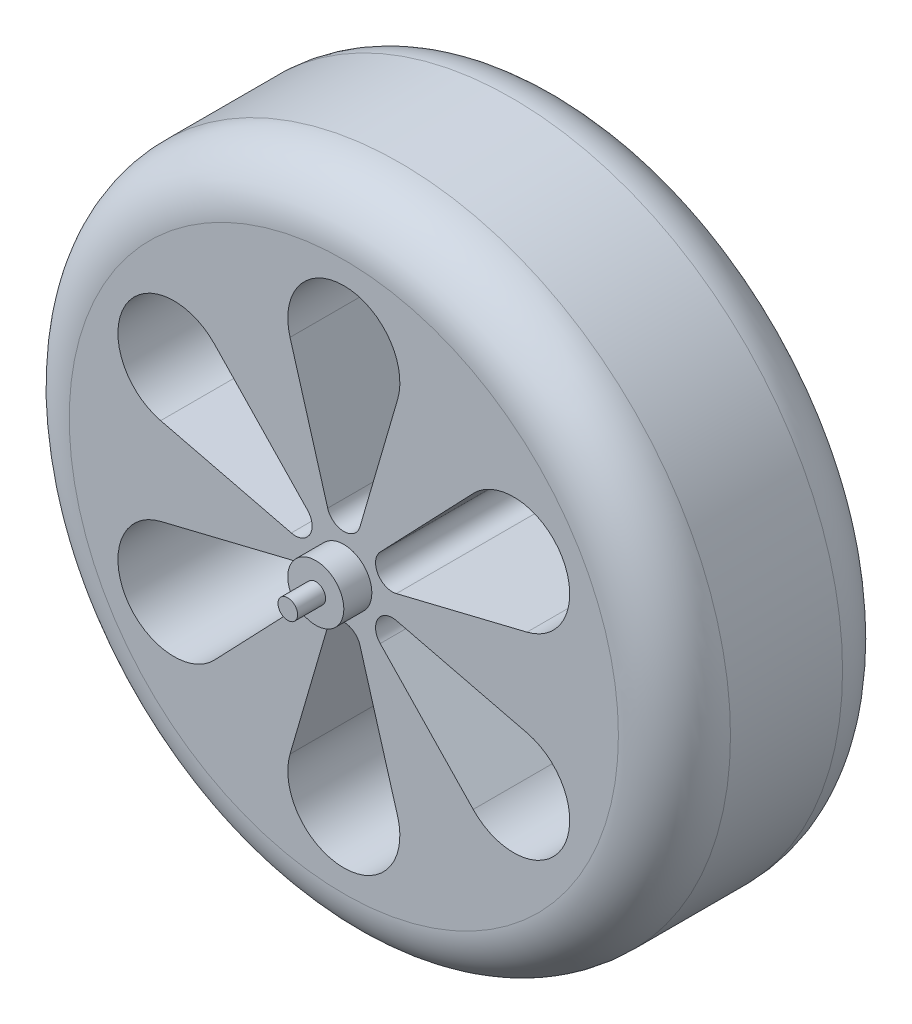
SolidWorks part; units mm, degrees
ref_plane "前视基准面" through (0, 0, 0) normal (0, 0, 1) x (1, 0, 0)
ref_plane "上视基准面" through (0, 0, 0) normal (0, 1, 0) x (1, 0, 0)
ref_plane "右视基准面" through (0, 0, 0) normal (1, 0, 0) x (0, 0, -1)
sketch "草图1" plane through (0, 0, 0) normal (0, 0, 1) x (1, 0, 0)
  circle A0 centre (0, 0) radius 59
  dimension "D1" = 118
extrude "凸台-拉伸1" add sketch "草图1" along normal blind 40
fillet "圆角1" radius 10 2 edges at (59, 0, 0) (59, 0, 40)
sketch "草图2" plane through (0, 0, 40) normal (0, 0, 1) x (1, 0, 0)
  circle A0 centre (0, 0) radius 5
  dimension "D1" = 10
extrude "凸台-拉伸2" add sketch "草图2" along normal blind 5
sketch "草图3" plane through (0, 0, 45) normal (0, 0, 1) x (1, 0, 0)
  circle A0 centre (0, 0) radius 1.75
  dimension "D1" = 3.5
extrude "凸台-拉伸3" add sketch "草图3" along normal blind 5
sketch "草图4" plane through (0, 0, 40) normal (0, 0, 1) x (1, 0, 0)
  line L0 (-9.6, 32.2) -> (-2.88, 9.16)
  line L1 (9.6, 32.2) -> (2.88, 9.16)
  arc A0 (9.6, 32.2) -> (-9.6, 32.2) centre (0, 35) ccw
  arc A1 (-2.88, 9.16) -> (2.88, 9.16) centre (0, 10) ccw
  dimension "D1" = 20
  dimension "D2" = 6
  dimension "D3" = 10
  dimension "D4" = 25
extrude "切除-拉伸1" cut sketch "草图4" against normal through all
pattern_circular "阵列(圆周)1" count 6 over 360 about axis through (0, 0, 0) along (0, 0, 1) of "切除-拉伸1"
